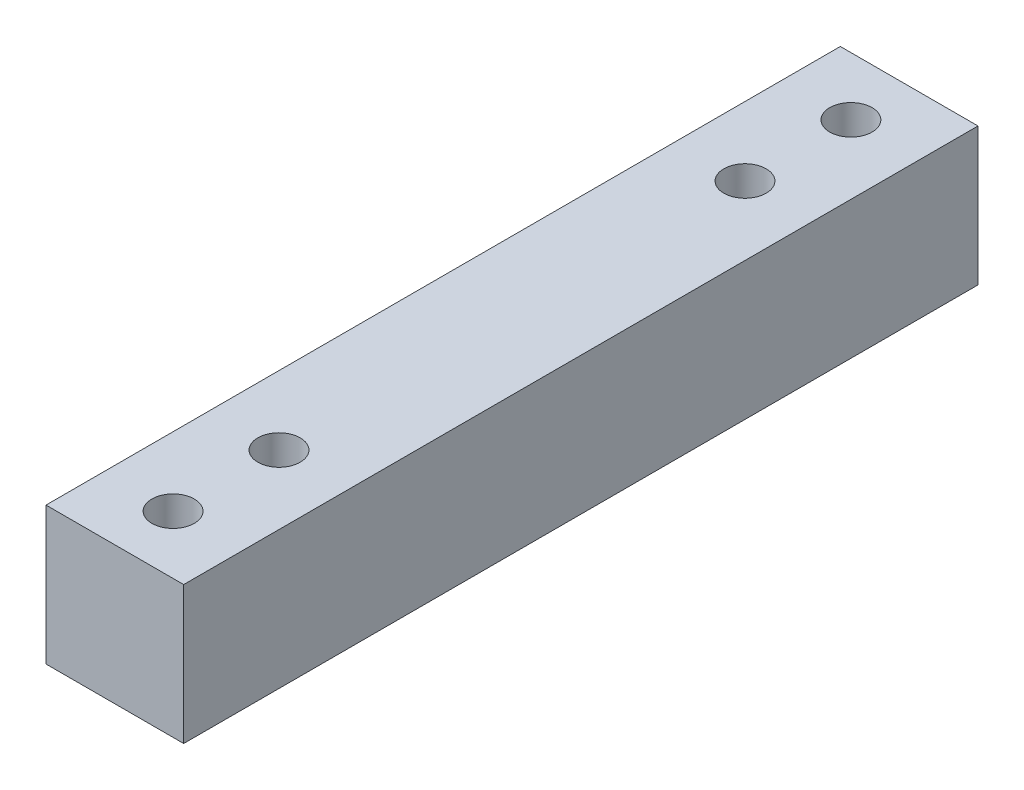
SolidWorks part; units mm, degrees
ref_plane "Front Plane" through (0, 0, 0) normal (0, 0, 1) x (1, 0, 0)
ref_plane "Top Plane" through (0, 0, 0) normal (0, 1, 0) x (1, 0, 0)
ref_plane "Right Plane" through (0, 0, 0) normal (1, 0, 0) x (0, 0, -1)
sketch "Sketch1" plane through (0, 0, 0) normal (0, 0, 1) x (1, 0, 0)
  line L1 (-6.5, -6.5) -> (6.5, -6.5)
  line L2 (-6.5, -6.5) -> (-6.5, 6.5)
  line L3 (-6.5, 6.5) -> (6.5, 6.5)
  line L4 (6.5, -6.5) -> (6.5, 6.5)
  line L5 (-6.5, -6.5) -> (6.5, 6.5) construction
  line L6 (-6.5, 6.5) -> (6.5, -6.5) construction
  point P1 (0, 0)
  dimension "D1" = 13
  dimension "D2" = 13
extrude "Boss-Extrude1" add sketch "Sketch1" along normal blind 75
sketch "Sketch2" plane through (0, 6.5, 0) normal (0, 1, 0) x (1, 0, 0)
  line L0 (0, 0) -> (0, -75) construction
  line L1 (6.5, -75) -> (-6.5, -75) construction
  line L2 (0, -37.5) -> (18.0138, -37.5) construction
  circle A0 centre (0, -69.5) radius 2
  circle A1 centre (0, -59.5) radius 2
  circle A2 centre (0, -5.5) radius 2
  circle A3 centre (0, -15.5) radius 2
  dimension "D1" = 4
  dimension "D2" = 4
  dimension "D3" = 5.5
  dimension "D4" = 10
extrude "Cut-Extrude1" cut sketch "Sketch2" against normal blind 75
